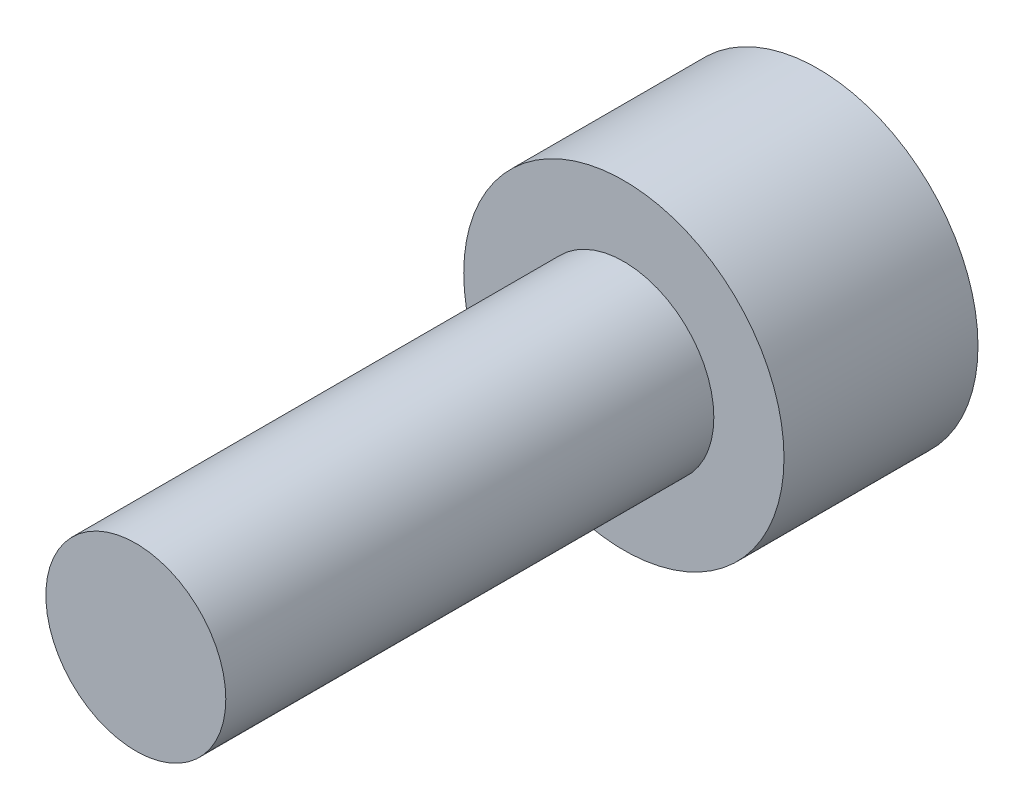
SolidWorks part; units mm, degrees
ref_plane "Front Plane" through (0, 0, 0) normal (0, 0, 1) x (1, 0, 0)
ref_plane "Top Plane" through (0, 0, 0) normal (0, 1, 0) x (1, 0, 0)
ref_plane "Right Plane" through (0, 0, 0) normal (1, 0, 0) x (0, 0, -1)
sketch "Sketch1" plane through (0, 0, 0) normal (0, 0, 1) x (1, 0, 0)
  circle A0 centre (0, 0) radius 2.625
  dimension "D1" = 5.25
extrude "Boss-Extrude1" add sketch "Sketch1" along normal blind 3.18 contours A0
sketch "Sketch2" plane through (0, 0, 3.18) normal (0, 0, 1) x (1, 0, 0)
  circle A0 centre (0, 0) radius 1.475
  dimension "D1" = 2.95
extrude "Boss-Extrude2" add sketch "Sketch2" along normal blind 8
